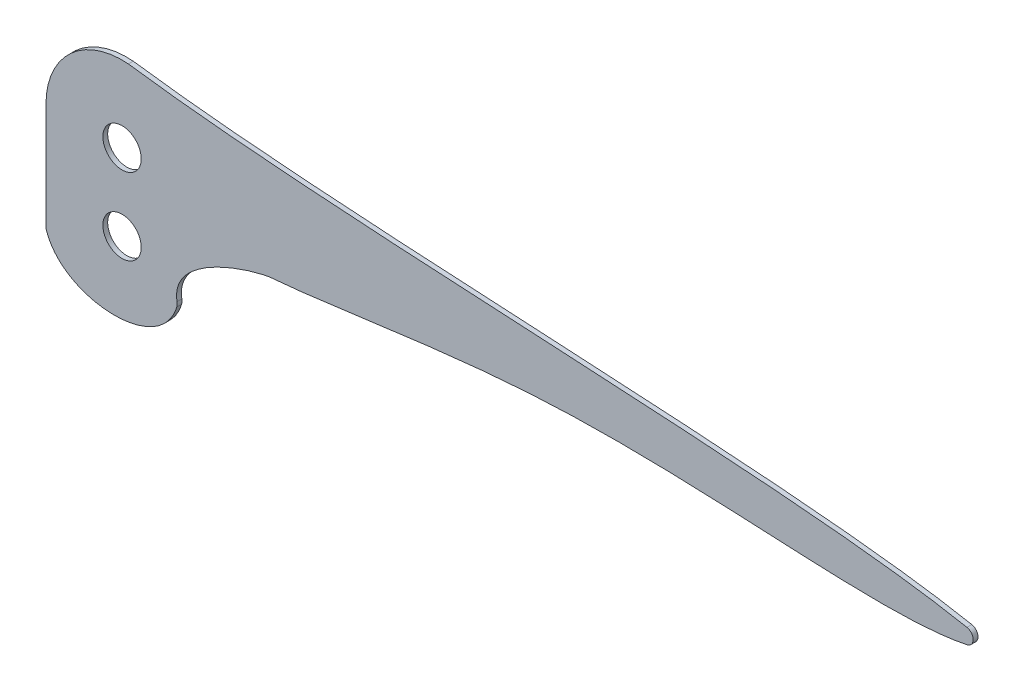
SolidWorks part; units mm, degrees
ref_plane "Front Plane" through (0, 0, 0) normal (0, 0, 1) x (1, 0, 0)
ref_plane "Top Plane" through (0, 0, 0) normal (0, 1, 0) x (1, 0, 0)
ref_plane "Right Plane" through (0, 0, 0) normal (1, 0, 0) x (0, 0, -1)
sketch "Sketch1" plane through (0, 0, 0) normal (0, 0, 1) x (1, 0, 0)
  line L0 (0, 0) -> (0, -25.4) construction
  line L1 (-25.1919, 0) -> (-25.1919, -35.2154)
  arc A1 (279.8894, 2.3729) -> (279.9348, -2.6026) centre (279.4, -0.1195) cw
  arc A2 (2.0902, 25.105) -> (-25.1919, 0) centre (0, 0) ccw
  circle A5 centre (0, -25.4) radius 6.35
  circle A6 centre (0, 0) radius 6.35
  arc A8 (18.2122, -35.0564) -> (18.1176, -36.6407) centre (14.8556, -35.6511) cw
  arc A9 (-25.1919, -35.2154) -> (-25.0041, -36.3312) centre (-21.783, -35.2154) ccw
  spline S0 degree 3 poles (2.0902, 25.105) (29.3726, 21.3189) (128.0417, 14.5406) (239.5484, 10.2935) (279.8894, 2.3729) knots 0.008543 0.008543 0.008543 0.008543 0.340595 0.941395 0.941395 0.941395 0.941395
  spline S1 degree 3 poles (50.3146, -12.4878) (67.829, -11.2174) (162.8512, 6.0974) (250.0383, -9.0418) (279.9348, -2.6026) knots 0.235846 0.235846 0.235846 0.235846 0.495201 0.941477 0.941477 0.941477 0.941477
  spline S2 degree 3 poles (18.2122, -35.0564) (15.7223, -21.0033) (45.0837, -12.5774) (50.3146, -12.4878) knots 0.243689 0.243689 0.243689 0.243689 1 1 1 1
  spline S3 degree 3 poles (-25.0041, -36.3312) (-24.3022, -38.3573) (-17.5003, -49.4729) (6.4866, -52.353) (16.8283, -40.8908) (18.1176, -36.6407) knots 0.011286 0.011286 0.011286 0.011286 0.130988 0.750185 0.983992 0.983992 0.983992 0.983992
  point P1 (-21.7987, -41.7245)
  point P3 (76.2, 0)
  point P10 (10.3556, -46.1234)
  dimension "D1" = 3.4089
  dimension "D2" = 2.54
  dimension "D3" = 12.7
  dimension "D4" = 12.7
  dimension "D6" = 279.4
extrude "Boss-Extrude1" add sketch "Sketch1" along normal blind 1.6002
